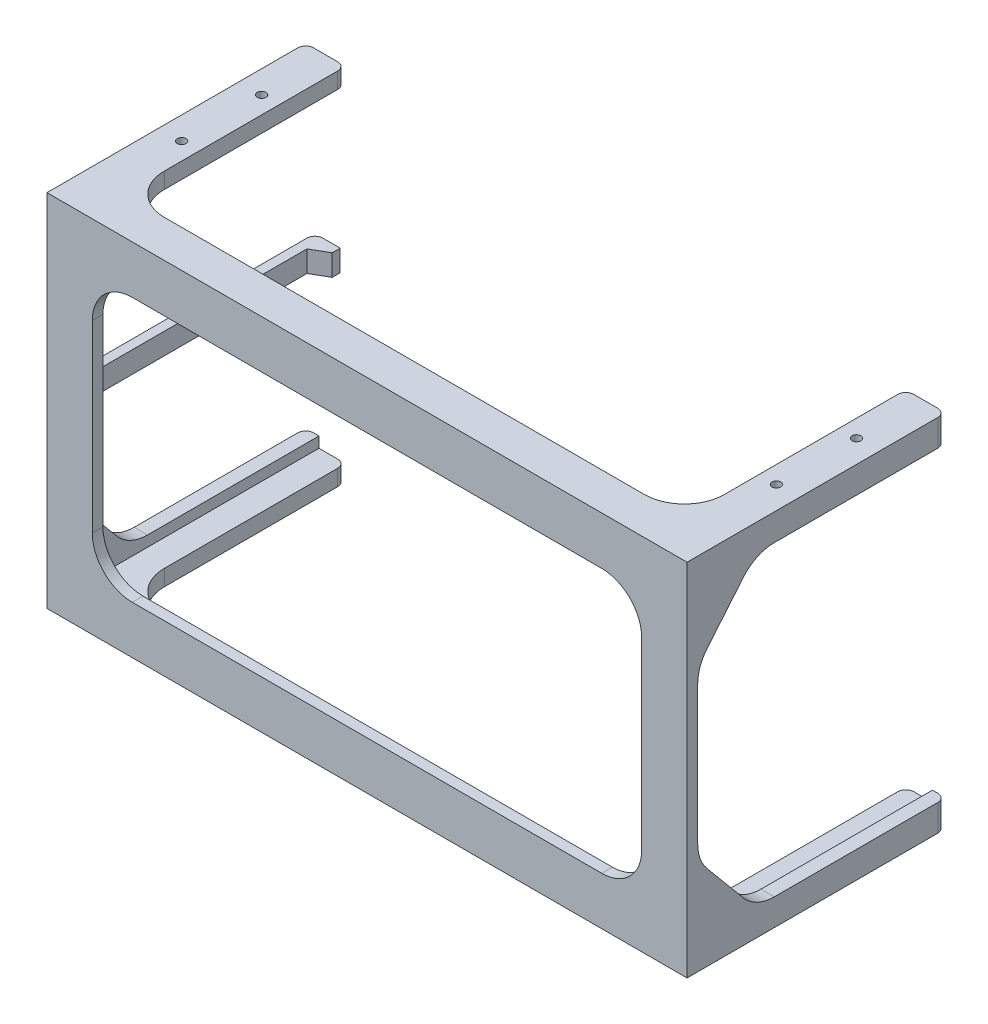
SolidWorks part; units mm, degrees
material "PLA Polyacetic Acid"
ref_plane "Front Plane" through (0, 0, 0) normal (0, 0, 1) x (1, 0, 0)
ref_plane "Top Plane" through (0, 0, 0) normal (0, 1, 0) x (1, 0, 0)
ref_plane "Right Plane" through (0, 0, 0) normal (1, 0, 0) x (0, 0, -1)
sketch "Sketch1" plane through (0, 0, 0) normal (0, 0, 1) x (1, 0, 0)
  line L0 (-103, -49.5) -> (-103, 49.5)
  line L1 (-115, -61.5) -> (115, -61.5)
  line L2 (-115, -61.5) -> (-115, 61.5)
  line L3 (-115, 61.5) -> (115, 61.5)
  line L4 (115, -61.5) -> (115, 61.5)
  line L5 (-115, -61.5) -> (115, 61.5) construction
  line L6 (-115, 61.5) -> (115, -61.5) construction
  line L7 (-103, 49.5) -> (103, 49.5)
  line L8 (103, -49.5) -> (103, 49.5)
  line L9 (-103, -49.5) -> (103, -49.5)
  point P0 (0, 0)
  dimension "D1" = 123
  dimension "D2" = 230
  dimension "D3" = 12
extrude "Boss-Extrude1" add sketch "Sketch1" along normal blind 4
sketch "Sketch2" plane through (0, 61.5, 0) normal (0, 1, 0) x (1, 0, 0)
  line L0 (0, -4) -> (0, 39.233) construction
  line L1 (-115, -4) -> (115, -4)
  line L2 (-115, -4) -> (-115, 10)
  line L3 (-105, 10) -> (105, 10)
  line L4 (115, -4) -> (115, 10)
  line L5 (-115, 10) -> (-105, 10) construction
  line L6 (-115, 10) -> (-115, 93)
  line L7 (-115, 93) -> (-105, 93)
  line L8 (-105, 10) -> (-105, 93)
  line L9 (115, -4) -> (-115, -4) construction
  line L10 (105, 10) -> (105, 93)
  line L11 (115, 93) -> (105, 93)
  line L12 (115, 10) -> (115, 93)
  line L13 (115, 10) -> (105, 10) construction
  line L14 (115, -4) -> (115, 10)
  line L15 (-115, 10) -> (-105, 10) construction
  line L16 (105, 10) -> (115, 10) construction
  line L17 (115, 0) -> (-115, 0) construction
  point P1 (-115, -4)
  point P18 (113.8653, 8.1789)
  line M7 (115, 0) -> (-115, 0)
  line M8 (-115, 0) -> (-115, -4)
  line M9 (-115, -4) -> (115, -4)
  line M10 (115, -4) -> (115, 0)
  dimension "D1" = 10
  dimension "D2" = 10
  dimension "D3" = 93
extrude "Boss-Extrude2" add sketch "Sketch2" along normal blind 6 contours L4 L12 L11 L10 L3 L8 L7 L6 L2 M7 | M10 M7 M8 M9
mirror "Mirror1" about plane through (0, 0, 0) normal (0, 1, 0) of "Boss-Extrude2"
sketch "Sketch3" plane through (-115, 0, 0) normal (-1, 0, 0) x (0, 0, 1)
  line L0 (-25, 61.5) -> (0, 31.5)
  line L1 (0, 61.5) -> (-25, 61.5) construction
  line L2 (0, 61.5) -> (0, 31.5) construction
  line L5 (0, 0) -> (-30.8852, 0) construction
  line L6 (0, -61.5) -> (0, -31.5)
  line L7 (0, -61.5) -> (-25, -61.5)
  line L8 (-25, -61.5) -> (0, -31.5)
  line L9 (-93, 61.5) -> (-93, 57.5)
  line L10 (-93, 57.5) -> (-21.6667, 57.5)
  line L11 (-93, -57.5) -> (-21.6667, -57.5)
  line L12 (-93, -61.5) -> (-93, -57.5)
  line L17 (0, 61.5) -> (0, -61.5)
  line L18 (0, -61.5) -> (-93, -61.5)
  line L19 (-93, -61.5) -> (-93, -67.5)
  line L20 (-93, -67.5) -> (4, -67.5)
  line L21 (4, -67.5) -> (4, 67.5)
  line L22 (4, 67.5) -> (-93, 67.5)
  line L23 (-93, 67.5) -> (-93, 61.5)
  line L24 (-93, 61.5) -> (0, 61.5)
  line L25 (0, 61.5) -> (0, -61.5)
  line L26 (0, -61.5) -> (-93, -61.5)
  line L27 (-93, -61.5) -> (-93, -67.5)
  line L28 (-93, -67.5) -> (4, -67.5)
  line L29 (4, -67.5) -> (4, 67.5)
  line L30 (4, 67.5) -> (-93, 67.5)
  line L31 (-93, 67.5) -> (-93, 61.5)
  line L32 (-93, 61.5) -> (0, 61.5)
  line M1 (0, 61.5) -> (0, -61.5)
  line M2 (0, -61.5) -> (-93, -61.5)
  line M3 (-93, -61.5) -> (-93, -67.5)
  line M4 (-93, -67.5) -> (4, -67.5)
  line M5 (4, -67.5) -> (4, 67.5)
  line M6 (4, 67.5) -> (-93, 67.5)
  line M7 (-93, 67.5) -> (-93, 61.5)
  line M8 (-93, 61.5) -> (0, 61.5)
  dimension "D1" = 30
  dimension "D2" = 25
  dimension "D3" = 0
  dimension "D4" = 4
extrude "Boss-Extrude3" add sketch "Sketch3" along normal blind 5 contours M8 M1 M2 M3 M4 M5 M6 M7 | L0 M8 M1 | L8 M2 M1 | L9 L10 L0 M8 | L12 L8 L11 M2
mirror "Mirror2" about plane through (0, 0, 0) normal (1, 0, 0) of "Boss-Extrude3"
fillet "Fillet1" radius 15 16 edges at (117.5, 57.5, -21.6667) (117.5, -57.5, -21.6667) (117.5, -31.5, 0) (117.5, 31.5, 0) (-103, -49.5, 2) (103, -49.5, 2) (103, 49.5, 2) (-103, 49.5, 2) (105, 64.5, -10) (-105, 64.5, -10) (-105, -64.5, -10) (105, -64.5, -10) (-117.5, 57.5, -21.6667) (-117.5, 31.5, 0) (-117.5, -31.5, 0) (-117.5, -57.5, -21.6667)
sketch "Sketch4" plane through (0, 0, 0) normal (0, 1, 0) x (1, 0, 0)
  line L0 (115, 0) -> (120, 0) construction
  line L1 (-120, 96.4641) -> (-116.5, 96.4641)
  line L2 (-120, 96.4641) -> (-120, 0)
  line L3 (-120, 0) -> (-116.5, 0)
  line L4 (-116.5, 96.4641) -> (-116.5, 0)
  line L6 (-116.5, 90) -> (-110.5, 93.4641)
  line L7 (-110.5, 93.4641) -> (-110.5, 96.4641)
  line L8 (-110.5, 96.4641) -> (-116.5, 96.4641)
  line L11 (0, 0) -> (0, 73.181) construction
  point P6 (0, 0)
  point P7 (0, 0)
  dimension "D1" = 3.5
  dimension "D2" = 3
  dimension "D3" = 60
  dimension "D4" = 90
  dimension "D5" = 221
extrude "Boss-Extrude4" add sketch "Sketch4" along normal mid plane 8 contours L7 L8 L4 L6
fillet "Fillet2" radius 5 2 edges at (-118.25, -4, 0) (-118.25, 4, 0)
fillet "Fillet3" radius 3 9 edges at (120, 62.5, -93) (120, -62.5, -93) (105, 64.5, -93) (-120, 0, -96.4641) (-105, 64.5, -93) (-105, -64.5, -93) (105, -64.5, -93) (-120, -62.5, -93) (-120, 62.5, -93)
hole_wizard "CSK for #4 Flat Head Machine Screw1" positions "Sketch5" profile "Sketch6" countersink size "#4" standard "ANSI Inch" end condition up to next
sketch "Sketch5" plane through (0, 61.5, 0) normal (0, -1, 0) x (1, 0, 0)
  line L0 (111.5, -68) -> (111.5, -38) construction
  line L3 (111.5, -68) -> (111.5, -93) construction
  line L4 (115, -93) -> (108, -93) construction
  line L6 (0, 0) -> (0, -52.6747) construction
  line L8 (115, 0) -> (-115, 0) construction
  point P0 (111.5, -68)
  point P2 (111.5, -38)
  point P21 (-111.5, -38)
  point P22 (-111.5, -68)
  point P24 (0, 0)
  dimension "D1" = 30
  dimension "D2" = 25
sketch "Sketch6" plane through (111.5, 61.5, -68) normal (1, 0, 0) x (0, 0, -1)
  line L0 (0, 0) -> (0, 6)
  line L1 (0, 6) -> (1.6319, 6)
  line L2 (1.6319, 6) -> (1.6319, 2.4098)
  line L3 (1.6319, 2.4098) -> (2.8575, 1)
  line L4 (2.8575, 1) -> (2.8575, 0)
  line L6 (2.8575, 0) -> (0, 0)
  line L7 (-1.632, 2.4098) -> (-2.8575, 1) construction
  line L11 (0, -6.35) -> (0, 107.95) construction
  dimension "Thru Hole Dia." = 3.2639
  dimension "Thru Hole Depth" = 6
  dimension "C'Sink Dia." = 5.715
  dimension "C'Sink Angle" = 82
  dimension "Head Clearance" = 1
